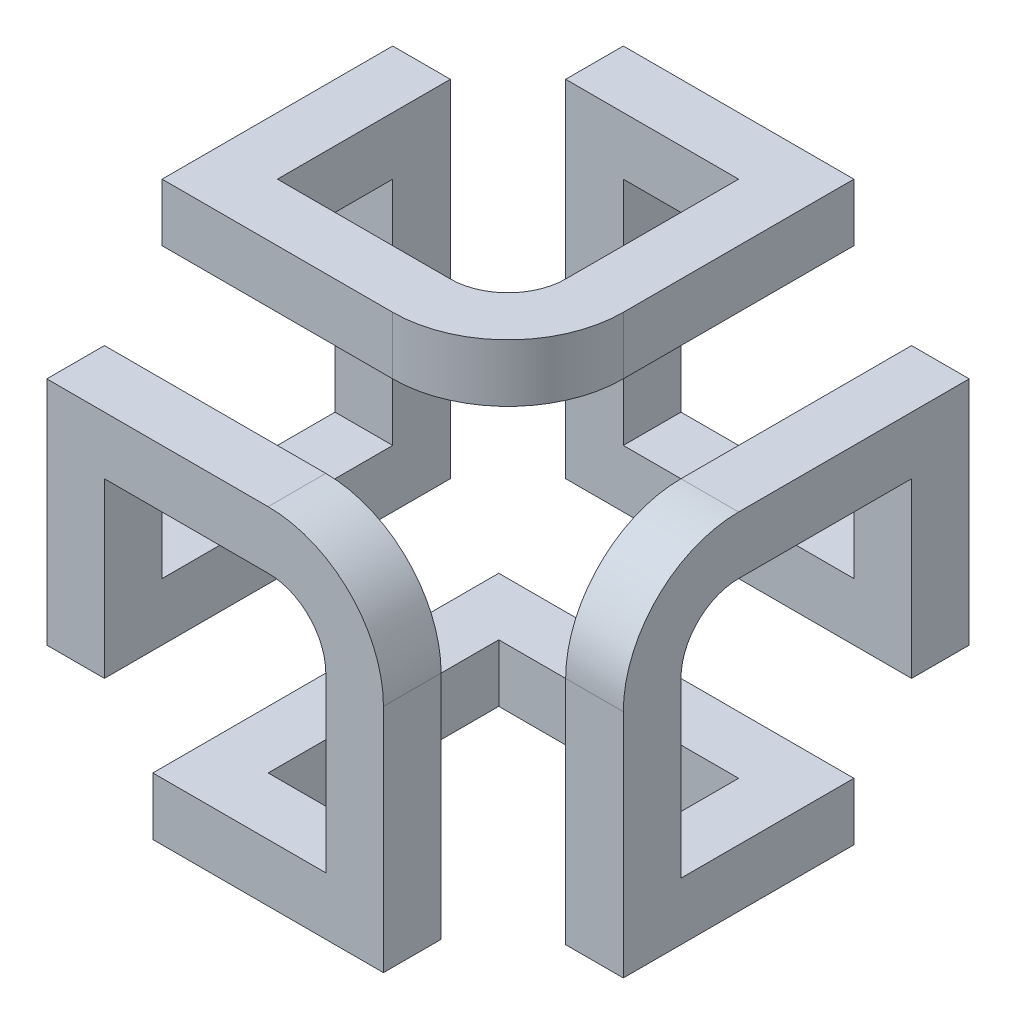
SolidWorks part; units mm, degrees
ref_plane "前视基准面" through (0, 0, 0) normal (0, 0, 1) x (1, 0, 0)
ref_plane "上视基准面" through (0, 0, 0) normal (0, 1, 0) x (1, 0, 0)
ref_plane "右视基准面" through (0, 0, 0) normal (1, 0, 0) x (0, 0, -1)
other "Configuration Table"
sketch "草图1" plane through (0, 0, 0) normal (0, 0, 1) x (1, 0, 0)
  line L8 (0, 20) -> (0, 60)
  line L9 (0, 0) -> (58.3965, 0) construction
  line L10 (0, 0) -> (0, 60) construction
  line L11 (0, 60) -> (58.3965, 60) construction
  line L12 (58.3965, 0) -> (58.3965, 60) construction
  line L13 (0, 60) -> (58.3965, 60)
  line L14 (58.3965, 60) -> (58.3965, 0)
  line L17 (48.3965, 50) -> (10, 50)
  line L18 (10, 50) -> (10, 20)
  line L19 (10, 20) -> (0, 20)
  line L20 (48.3965, 50) -> (48.3965, 10)
  line L21 (48.3965, 10) -> (18.3965, 10)
  line L22 (18.3965, 10) -> (18.3965, 0)
  line L23 (18.3965, 0) -> (58.3965, 0)
  line L25 (18.3965, 10) -> (28.3965, 10)
  line L26 (18.3965, 10) -> (18.3965, 0)
  line L27 (18.3965, 0) -> (28.3965, 0)
  line L28 (28.3965, 10) -> (28.3965, 0)
  line L29 (0, 30) -> (10, 30)
  line L30 (0, 30) -> (0, 20)
  line L31 (0, 20) -> (10, 20)
  line L32 (10, 30) -> (10, 20)
  dimension "D1" = 60
  dimension "D2" = 58.3965
  dimension "D3" = 40
  dimension "D4" = 10
  dimension "D5" = 10
  dimension "D6" = 10
  dimension "D7" = 10
  dimension "D8" = 40
  dimension "D9" = 10
  dimension "D10" = 10
extrude "凸台-拉伸1" add sketch "草图1" against normal blind 10 contours L8 L29 L18 L17 L20 L21 L28 L23 L14 L13 | L29 L8 L19 L18 | L28 L21 L22 L23
sketch "草图2" plane through (0, 0, 0) normal (-1, 0, 0) x (0, 0, 1)
  line L0 (0, 20) -> (-60, 20)
  line L1 (0, 20) -> (-60, 20) construction
  line L2 (0, 20) -> (0, 80) construction
  line L3 (0, 80) -> (-60, 80) construction
  line L4 (-60, 20) -> (-60, 80) construction
  line L5 (-60, 20) -> (-60, 80)
  line L6 (-60, 80) -> (-20, 80)
  line L7 (-20, 80) -> (-20, 70)
  line L8 (-20, 70) -> (-50, 70)
  line L9 (-50, 70) -> (-50, 30)
  line L10 (-50, 30) -> (-10, 30)
  line L11 (-10, 20) -> (-10, 60) construction
  line L12 (-10, 30) -> (-10, 60)
  line L13 (-10, 60) -> (0, 60)
  line L14 (0, 60) -> (0, 20)
  point P12 (-13.3255, 80)
  dimension "D1" = 60
  dimension "D2" = 60
  dimension "D3" = 10
  dimension "D4" = 10
  dimension "D5" = 10
  dimension "D6" = 40
extrude "凸台-拉伸2" add sketch "草图2" against normal blind 10 contours L14 L0 L5 L6 L7 L8 L9 L10 L12 L13
sketch "草图3" plane through (0, 80, 0) normal (0, 1, 0) x (1, 0, 0)
  line L0 (0, 60) -> (0, 20)
  line L1 (0, 20) -> (60, 20) construction
  line L2 (0, 20) -> (0, 80) construction
  line L3 (0, 80) -> (60, 80) construction
  line L4 (60, 20) -> (60, 80) construction
  line L5 (0, 20) -> (60, 20)
  line L6 (60, 20) -> (60, 80)
  line L7 (60, 80) -> (20, 80)
  line L8 (20, 80) -> (20, 70)
  line L9 (20, 70) -> (50, 70)
  line L10 (50, 70) -> (50, 30)
  line L11 (50, 30) -> (10, 30)
  line L12 (10, 60) -> (10, 20) construction
  line L13 (10, 30) -> (10, 60)
  line L14 (10, 60) -> (0, 60) construction
  line L15 (10, 60) -> (0, 60)
  dimension "D1" = 60
  dimension "D2" = 60
  dimension "D3" = 10
  dimension "D4" = 10
  dimension "D5" = 10
  dimension "D6" = 40
extrude "凸台-拉伸3" add sketch "草图3" against normal blind 10
sketch "草图4" plane through (0, 0, -80) normal (0, 0, -1) x (-1, 0, 0)
  line L0 (-60, 80) -> (-20, 80)
  line L1 (-20, 80) -> (-80, 80) construction
  line L2 (-20, 80) -> (-20, 20) construction
  line L3 (-20, 20) -> (-80, 20) construction
  line L4 (-80, 80) -> (-80, 20) construction
  line L5 (-20, 80) -> (-20, 20)
  line L6 (-20, 20) -> (-80, 20)
  line L7 (-80, 20) -> (-80, 60)
  line L8 (-80, 60) -> (-70, 60)
  line L9 (-70, 60) -> (-70, 30)
  line L10 (-70, 30) -> (-30, 30)
  line L11 (-30, 30) -> (-30, 70)
  line L12 (-60, 70) -> (-20, 70) construction
  line L13 (-30, 70) -> (-60, 70)
  line L14 (-60, 70) -> (-60, 80)
  dimension "D1" = 60
  dimension "D2" = 60
  dimension "D3" = 10
  dimension "D4" = 10
  dimension "D5" = 10
  dimension "D6" = 40
extrude "凸台-拉伸4" add sketch "草图4" against normal blind 10
sketch "草图5" plane through (80, 0, 0) normal (1, 0, 0) x (0, 0, -1)
  line L0 (80, 60) -> (80, 20) construction
  line L1 (80, 60) -> (20, 60) construction
  line L2 (80, 60) -> (80, 0) construction
  line L3 (80, 0) -> (20, 0) construction
  line L4 (20, 60) -> (20, 0) construction
  line L5 (80, 60) -> (20, 60)
  line L6 (20, 60) -> (20, 0)
  line L7 (20, 0) -> (60, 0)
  line L8 (60, 0) -> (60, 10)
  line L9 (60, 10) -> (30, 10)
  line L10 (30, 10) -> (30, 50)
  line L11 (30, 50) -> (70, 50)
  line L12 (70, 60) -> (70, 20) construction
  line L13 (70, 50) -> (70, 20)
  line L14 (70, 20) -> (80, 20)
  line L15 (80, 20) -> (80, 60)
  dimension "D1" = 60
  dimension "D2" = 60
  dimension "D3" = 10
  dimension "D4" = 10
  dimension "D5" = 10
  dimension "D6" = 40
extrude "凸台-拉伸5" add sketch "草图5" against normal blind 10
sketch "草图6" plane through (0, 0, 0) normal (0, -1, 0) x (1, 0, 0)
  line L0 (18.3965, -10) -> (18.3965, -60)
  line L1 (18.3965, -60) -> (70, -60)
  line L2 (70, -20) -> (70, -60) construction
  line L3 (70, -60) -> (70, -50)
  line L4 (70, -50) -> (28.3965, -50)
  line L5 (28.3965, -50) -> (28.3965, -10)
  line L6 (18.3965, -10) -> (58.3965, -10) construction
  line L7 (28.3965, -10) -> (18.3965, -10)
  point P3 (0, 0)
  dimension "D1" = 10
  dimension "D2" = 10
extrude "凸台-拉伸6" add sketch "草图6" against normal blind 10
fillet "圆角3" radius 20 1 edges at (60, 75, -20)
fillet "圆角4" radius 10 1 edges at (50, 75, -30)
fillet "圆角5" radius 20 1 edges at (75, 60, -20)
fillet "圆角6" radius 20 1 edges at (58.3965, 60, -5)
fillet "圆角7" radius 10 1 edges at (48.3965, 50, -5)
fillet "圆角8" radius 10 1 edges at (75, 50, -30)
